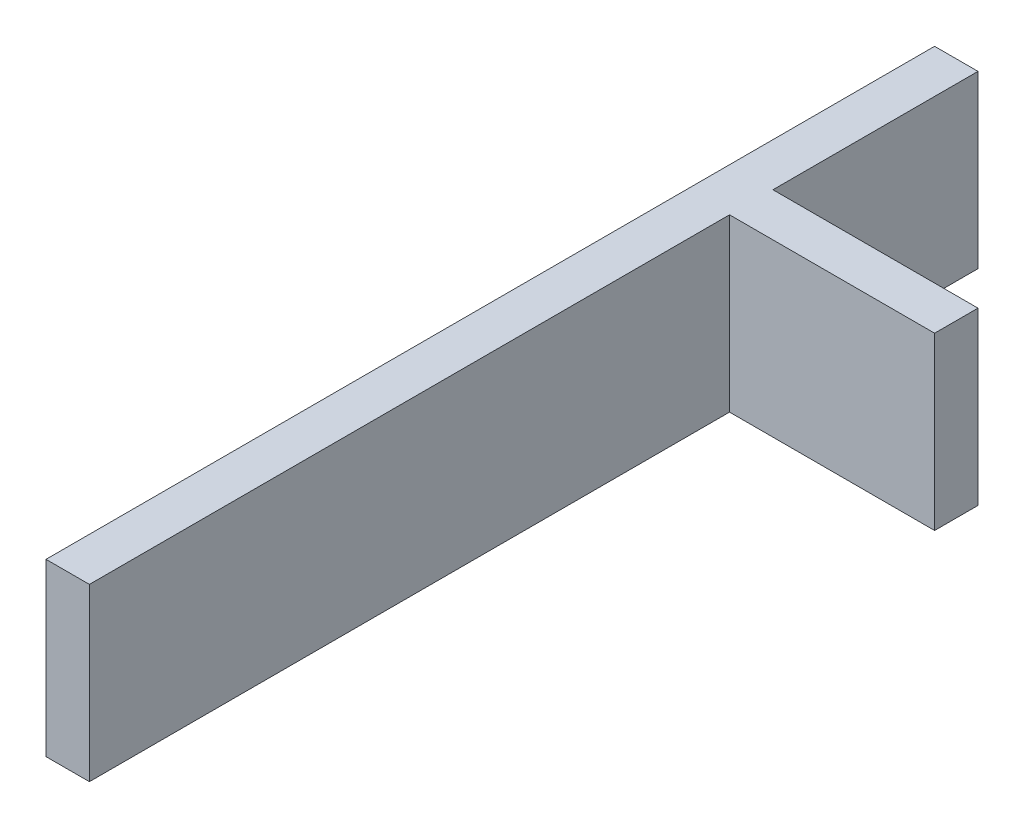
SolidWorks part; units mm, degrees
ref_plane "Alzado" through (0, 0, 0) normal (0, 0, 1) x (1, 0, 0)
ref_plane "Planta" through (0, 0, 0) normal (0, 1, 0) x (1, 0, 0)
ref_plane "Vista lateral" through (0, 0, 0) normal (1, 0, 0) x (0, 0, -1)
sketch "Croquis1" plane through (0, 0, 0) normal (0, 0, 1) x (1, 0, 0)
  line L1 (3.175, -12.5) -> (-3.175, -12.5)
  line L2 (3.175, -12.5) -> (3.175, 12.5)
  line L3 (3.175, 12.5) -> (-3.175, 12.5)
  line L4 (-3.175, -12.5) -> (-3.175, 12.5)
  line L5 (3.175, -12.5) -> (-3.175, 12.5) construction
  line L6 (3.175, 12.5) -> (-3.175, -12.5) construction
  point P0 (0, 0)
  dimension "D1" = 6.35
  dimension "D2" = 25
extrude "Saliente-Extruir1" add sketch "Croquis1" along normal blind 130
sketch "Croquis2" plane through (3.175, 0, 0) normal (1, 0, 0) x (0, 0, -1)
  line L0 (0, 0) -> (-30, 0) construction
  line L1 (-30, 12.5) -> (-30, -12.5)
  line L2 (-130, 12.5) -> (0, 12.5) construction
  line L3 (-130, -12.5) -> (0, -12.5) construction
  line L4 (-30, -12.5) -> (-36.35, -12.5)
  line L5 (-36.35, -12.5) -> (-36.35, 12.5)
  line L6 (-36.35, 12.5) -> (-30, 12.5)
  dimension "D1" = 30
  dimension "D2" = 6.35
extrude "Saliente-Extruir2" add sketch "Croquis2" along normal blind 30
